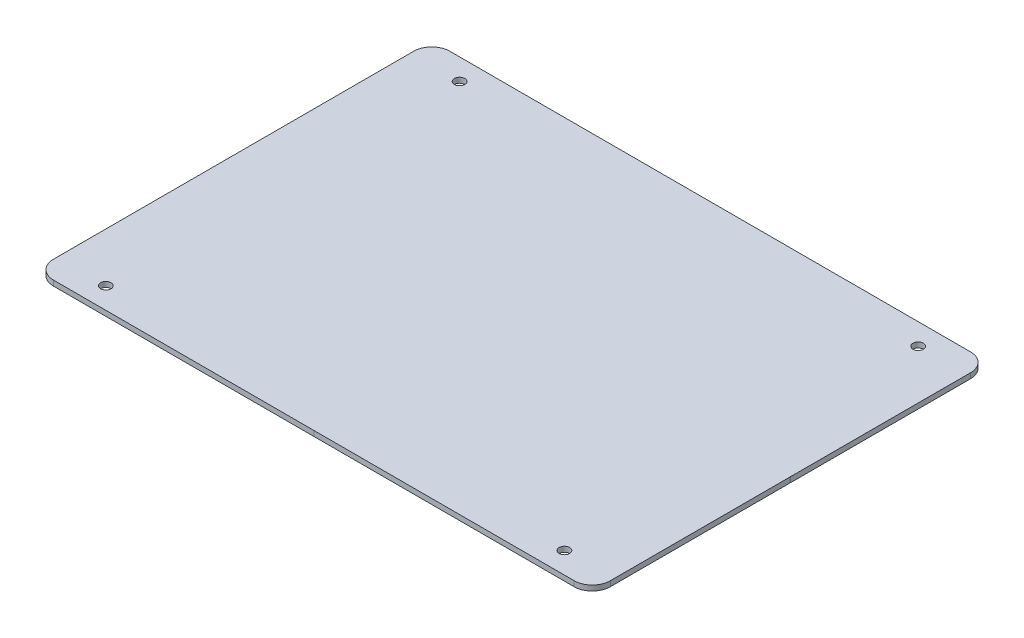
SolidWorks part; units mm, degrees
ref_plane "Ebene vorne" through (0, 0, 0) normal (0, 0, 1) x (1, 0, 0)
ref_plane "Ebene oben" through (0, 0, 0) normal (0, 1, 0) x (1, 0, 0)
ref_plane "Ebene rechts" through (0, 0, 0) normal (1, 0, 0) x (0, 0, -1)
sketch "Skizze1" plane through (0, 0, 0) normal (0, 1, 0) x (1, 0, 0)
  line L18 (-79.5, 60.5) -> (0.0001, 60.5)
  line L20 (85, 0) -> (85, 55)
  line L21 (0.0001, 60.5) -> (79.5, 60.5)
  line L22 (0, -60.5) -> (79.5, -60.5)
  line L23 (85, 0) -> (85, -55)
  line L24 (-79.5, -60.5) -> (0, -60.5)
  line L42 (-85, 55) -> (-85, -55)
  circle A40 centre (85, 0) radius 0.0635
  circle A46 centre (85, 0) radius 0.0635
  circle A98 centre (-70, -54) radius 1.6
  circle A101 centre (70, -54) radius 1.6
  circle A104 centre (70, 54) radius 1.6
  circle A107 centre (-70, 54) radius 1.6
  arc A110 (-79.5, 60.5) -> (-85, 55) centre (-79.5, 55) ccw
  arc A113 (85, 55) -> (79.5, 60.5) centre (79.5, 55) ccw
  arc A116 (79.5, -60.5) -> (85, -55) centre (79.5, -55) ccw
  arc A119 (-85, -55) -> (-79.5, -60.5) centre (-79.5, -55) ccw
extrude "Aufsatz-Linear austragen2" add sketch "Skizze1" along normal blind 1.6 contours L42 A119 L24 L22 A116 L23 A40 L20 A113 L21 L18 A110 A98 A101 A104 A107
